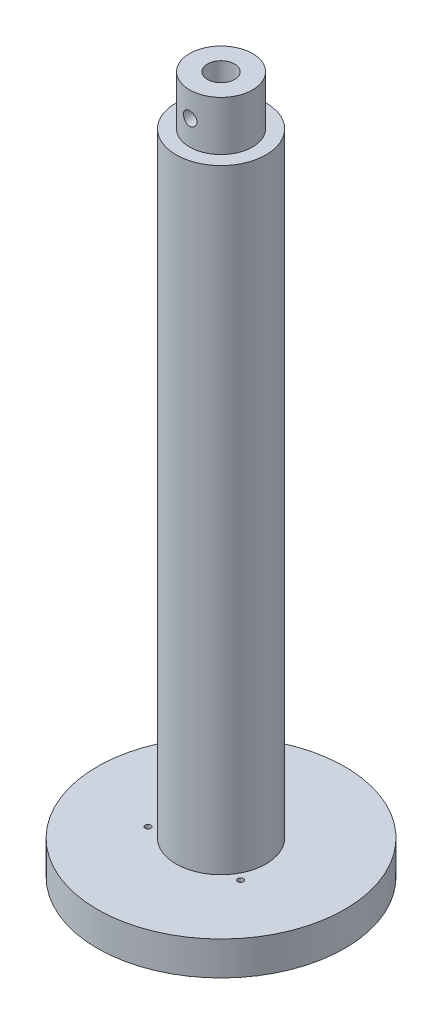
SolidWorks part; units mm, degrees
material "AISI 1045 Steel, cold drawn"
ref_plane "Front Plane" through (0, 0, 0) normal (0, 0, 1) x (1, 0, 0)
ref_plane "Top Plane" through (0, 0, 0) normal (0, 1, 0) x (1, 0, 0)
ref_plane "Right Plane" through (0, 0, 0) normal (1, 0, 0) x (0, 0, -1)
sketch "Sketch1" plane through (0, 0, 0) normal (0, 1, 0) x (1, 0, 0)
  circle A0 centre (0, 0) radius 55
  dimension "D1" = 110
extrude "Boss-Extrude1" add sketch "Sketch1" along normal mid plane 15 contours A0
sketch "Sketch2" plane through (0, 7.5, 0) normal (0, 1, 0) x (1, 0, 0)
  circle A0 centre (0, 0) radius 20
  dimension "D1" = 40
extrude "Boss-Extrude2" add sketch "Sketch2" along normal blind 273
sketch "Sketch3" plane through (0, 280.5, 0) normal (0, 1, 0) x (1, 0, 0)
  circle A0 centre (0, 0) radius 14
  dimension "D1" = 28
extrude "Boss-Extrude3" add sketch "Sketch3" along normal blind 22
sketch "Sketch4" plane through (0, -7.5, 0) normal (0, -1, 0) x (1, 0, 0)
  circle A0 centre (0, 0) radius 53
  dimension "D1" = 106
extrude "Cut-Extrude1" cut sketch "Sketch4" against normal blind 3
sketch "Sketch5" plane through (0, -4.5, 0) normal (0, -1, 0) x (1, 0, 0)
  circle A0 centre (0, 0) radius 6
  dimension "D1" = 12
extrude "Cut-Extrude2" cut sketch "Sketch5" against normal through all
sketch "Sketch7" plane through (0, 0, 0) normal (0, 0, 1) x (1, 0, 0)
  line L0 (14, 302.5) -> (-14, 302.5) construction
  line L1 (0, 291.5) -> (0, -17.1112) construction
  circle A0 centre (0, 291.5) radius 3
  dimension "D2" = 6
  dimension "D1" = 11
extrude "Cut-Extrude3" cut sketch "Sketch7" against normal through all both and the other way through all
sketch "Sketch9" plane through (0, 7.5, 0) normal (0, 1, 0) x (1, 0, 0)
  line L0 (0, 25) -> (0, 0) construction
  line L1 (-23.75, 0) -> (23.75, 0) construction
  line L2 (0, 23.75) -> (0, -23.75) construction
  circle A0 centre (0, 0) radius 23.75
  circle A1 centre (0, 23.75) radius 1.25
  circle A2 centre (-20.5681, -11.875) radius 1.25
  circle A3 centre (20.5681, -11.875) radius 1.25
  dimension "D1" = 47.5
  dimension "D2" = 2.5
  dimension "D3" = 2.5
  dimension "D4" = 120
  dimension "D5" = 120
hole_wizard "M3 Tapped Hole1" positions "Sketch10" profile "Sketch11" tap size "M3" standard "ISO"
sketch "Sketch10" plane through (0, 7.5, 0) normal (0, 1, 0) x (1, 0, 0)
  point P0 (-20.5681, -11.875)
  point P3 (20.5681, -11.875)
  point P6 (0, 23.75)
sketch "Sketch11" plane through (-20.5681, 7.5, 11.875) normal (1, 0, 0) x (0, 0, 1)
  line L0 (0, 0) -> (0, 8.7511)
  line L1 (0, 8.7511) -> (1.25, 8)
  line L2 (1.25, 8) -> (1.25, 0)
  line L5 (1.25, 0) -> (0, 0)
  line L10 (0, 8.7511) -> (-1.25, 8) construction
  line L11 (0, -6.35) -> (0, 107.95) construction
  dimension "Tap Drill Dia." = 2.5
  dimension "Tap Drill Depth" = 8
  dimension "Drill Angle" = 118
cosmetic thread "Hole Thread1" parameters "D1"=6, "D2"=3
cosmetic thread "Hole Thread2" parameters "D1"=6, "D2"=3
cosmetic thread "Hole Thread3" parameters "D1"=6, "D2"=3
